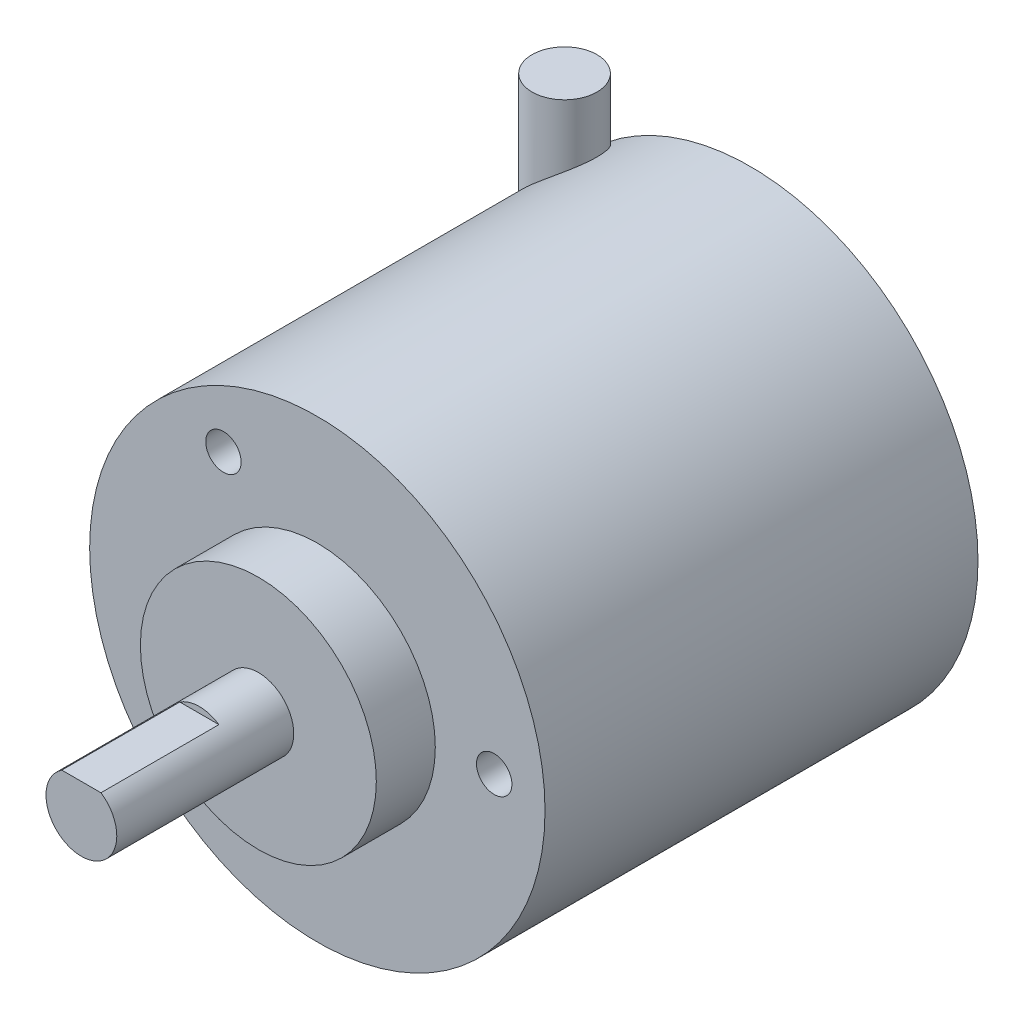
SolidWorks part; units mm, degrees
ref_plane "Front Plane" through (0, 0, 0) normal (0, 0, 1) x (1, 0, 0)
ref_plane "Top Plane" through (0, 0, 0) normal (0, 1, 0) x (1, 0, 0)
ref_plane "Right Plane" through (0, 0, 0) normal (1, 0, 0) x (0, 0, -1)
sketch "Sketch1" plane through (0, 0, 0) normal (0, 0, 1) x (1, 0, 0)
  circle A0 centre (-14.1274, 5.3793) radius 19.3
  dimension "D1" = 38.6
extrude "Boss-Extrude1" add sketch "Sketch1" along normal blind 36.7
sketch "Sketch3" plane through (0, 0, 36.7) normal (0, 0, 1) x (1, 0, 0)
  circle A0 centre (-14.1274, 5.3793) radius 10
  circle A1 centre (-14.1274, 5.3793) radius 19.3 construction
  dimension "D1" = 20
  dimension "D2" = 0
extrude "Boss-Extrude2" add sketch "Sketch3" along normal blind 5
sketch "Sketch4" plane through (0, 0, 41.7) normal (0, 0, 1) x (1, 0, 0)
  circle A0 centre (-14.1274, 5.3793) radius 3
  circle A1 centre (-14.1274, 5.3793) radius 10 construction
  dimension "D1" = 6
  dimension "D2" = 0
extrude "Boss-Extrude3" add sketch "Sketch4" along normal blind 15
sketch "Sketch5" plane through (0, 0, 36.7) normal (0, 0, 1) x (1, 0, 0)
  circle A0 centre (0.863, 5.9165) radius 1.5
  circle A1 centre (-14.1274, 5.3793) radius 3 construction
  circle A2 centre (-21.1574, -7.8714) radius 1.5
  circle A3 centre (-22.0878, 18.0927) radius 1.5
  point P10 (-14.1274, 5.3793)
  dimension "D1" = 3
  dimension "D2" = 15
  dimension "D3" = 3
ref_plane "Plane1" through (0, 24.6793, 0) normal (0, 1, 0) x (1, 0, 0)
sketch "Sketch8" plane through (0, 24.6793, 0) normal (0, 1, 0) x (1, 0, 0)
  circle A0 centre (-26.8321, -3.0426) radius 2.75
  dimension "D1" = 5.5
extrude "Boss-Extrude4" add sketch "Sketch8" against normal blind 15 from offset 3 separate body offset against normal yes
sketch "Sketch9" plane through (0, 21.6793, 0) normal (0, 1, 0) x (1, 0, 0)
  circle A0 centre (-26.8321, -3.0426) radius 2.75
extrude "Boss-Extrude5" add sketch "Sketch9" along normal blind 5
extrude "Cut-Extrude1" cut sketch "Sketch5" against normal blind 10
sketch "Sketch10" plane through (0, 0, 56.7) normal (0, 0, 1) x (1, 0, 0)
  line L0 (-15.7857, 7.8793) -> (-12.4691, 7.8793)
  circle A0 centre (-14.1274, 5.3793) radius 3
  circle M2 centre (-14.1274, 5.3793) radius 3
  dimension "D2" = 6
  dimension "D1" = 2.5
extrude "Cut-Extrude2" cut sketch "Sketch10" against normal blind 10 contours L0 M2
